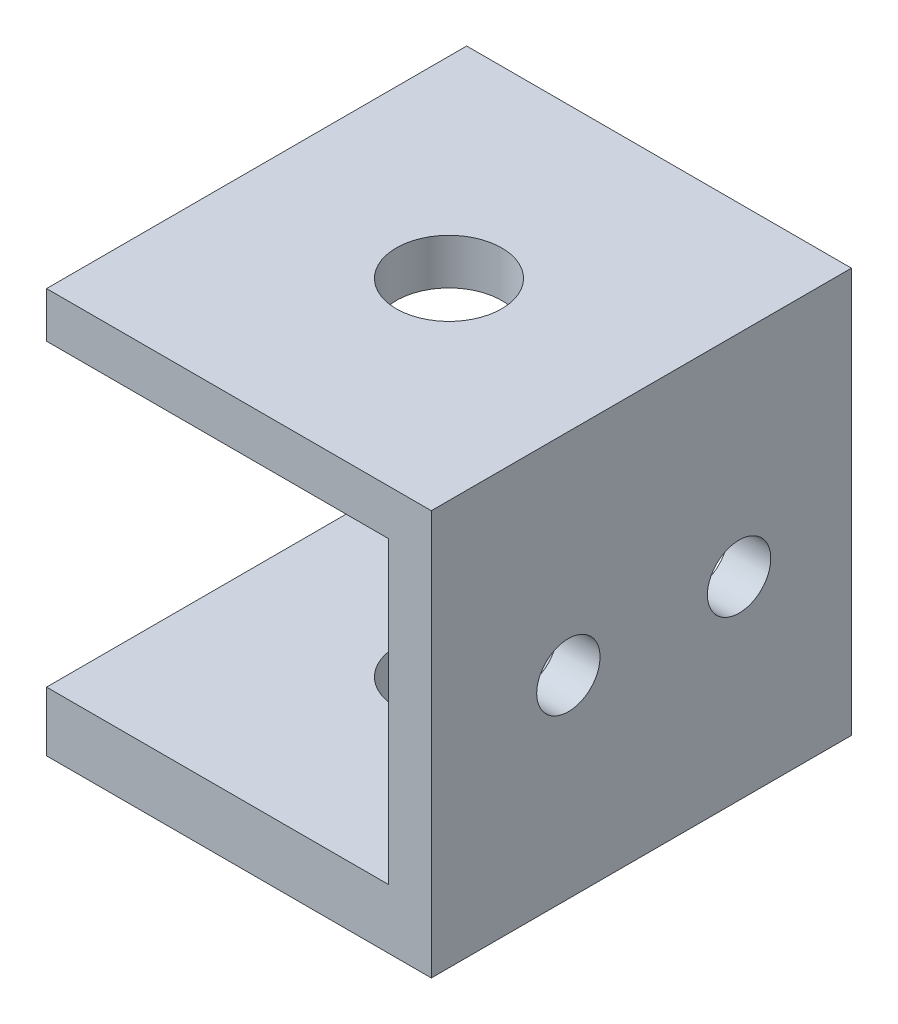
SolidWorks part; units mm, degrees
ref_plane "Plan de face" through (0, 0, 0) normal (0, 0, 1) x (1, 0, 0)
ref_plane "Plan de dessus" through (0, 0, 0) normal (0, 1, 0) x (1, 0, 0)
ref_plane "Plan de droite" through (0, 0, 0) normal (1, 0, 0) x (0, 0, -1)
sketch "Esquisse1" plane through (0, 0, 0) normal (0, 0, 1) x (1, 0, 0)
  line L1 (0, 0) -> (45.7912, 0)
  line L2 (0, 0) -> (0, 48.1628)
  line L3 (0, 48.1628) -> (45.7912, 48.1628)
  line L4 (45.7912, 0) -> (45.7912, 48.1628)
extrude "Boss.-Extru.1" add sketch "Esquisse1" along normal blind 50
sketch "Esquisse6" plane through (0, 0, 50) normal (0, 0, 1) x (1, 0, 0)
  line L0 (0, 48.1628) -> (0, 0) construction
  line L1 (0, 42.7368) -> (40.7205, 42.7368)
  line L2 (0, 42.7368) -> (0, 7.0871)
  line L3 (0, 7.0871) -> (40.7205, 7.0871)
  line L4 (40.7205, 42.7368) -> (40.7205, 7.0871)
  line L5 (45.7912, 0) -> (45.7912, 48.1628) construction
  dimension "D1" = 5.426
  dimension "D2" = 5.0707
  dimension "D3" = 7.0871
extrude "Enlèv. mat.-Extru.2" cut sketch "Esquisse6" against normal through all
sketch "Esquisse7" plane through (0, 48.1628, 0) normal (0, 1, 0) x (1, 0, 0)
  line L0 (0, -50) -> (0, 0) construction
  line L1 (45.7912, 0) -> (0, 0) construction
  circle A0 centre (22.8956, -25) radius 6.2771
  point P4 (0, -25)
  point P7 (22.8956, 0)
  point P8 (0, 0)
  dimension "D1" = 12.5543
extrude "Enlèv. mat.-Extru.3" cut sketch "Esquisse7" against normal through all
sketch "Esquisse8" plane through (40.7205, 0, 0) normal (-1, 0, 0) x (0, 0, 1)
  line L0 (0, 7.0871) -> (0, 42.7368) construction
  circle A0 centre (13.3723, 23.0592) radius 3.7694
  circle A1 centre (33.6888, 23.0592) radius 3.7694
  point P4 (0, 0)
  point P5 (0, 0)
  point P6 (0, 0)
  point P7 (0, 0)
  dimension "D2" = 7.5388
  dimension "D1" = 20.3165
  dimension "D3" = 19.6776
  dimension "D4" = 13.3723
extrude "Enlèv. mat.-Extru.4" cut sketch "Esquisse8" against normal through all
